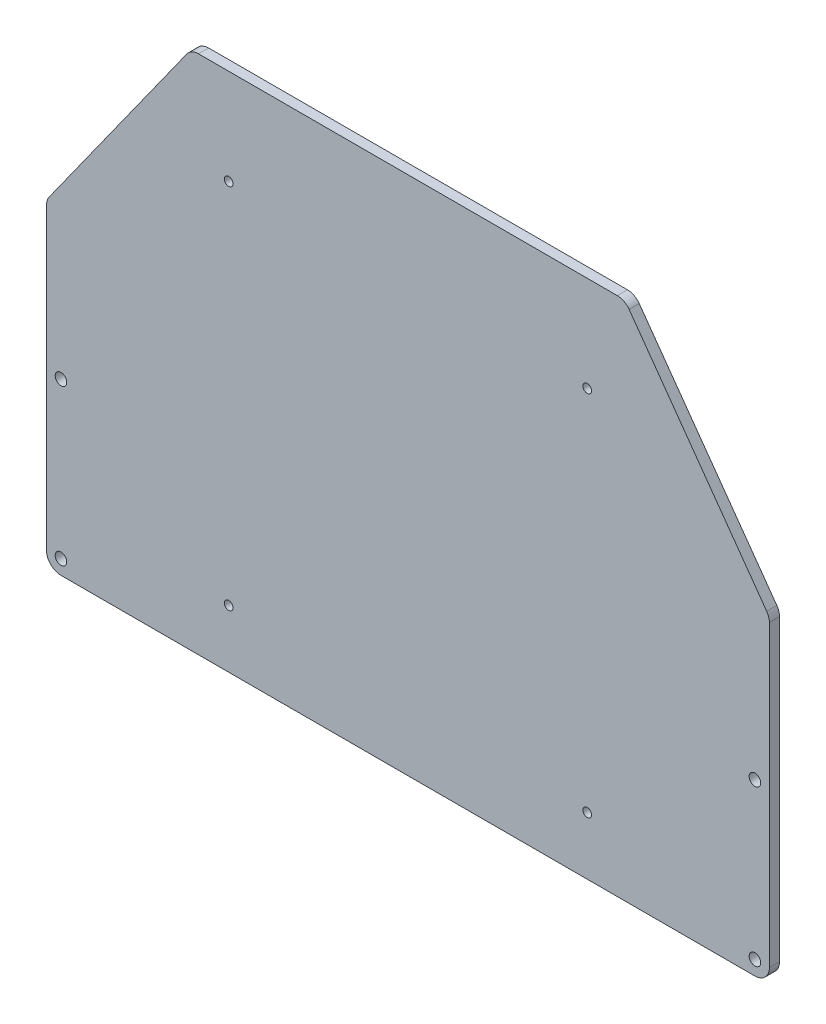
SolidWorks part; units mm, degrees
ref_plane "Plan de face" through (0, 0, 0) normal (0, 0, 1) x (1, 0, 0)
ref_plane "Plan de dessus" through (0, 0, 0) normal (0, 1, 0) x (1, 0, 0)
ref_plane "Plan de droite" through (0, 0, 0) normal (1, 0, 0) x (0, 0, -1)
sketch "Esquisse1" plane through (0, 0, 0) normal (0, 0, 1) x (1, 0, 0)
  line L1 (5, 0) -> (245, 0)
  line L2 (0, 5) -> (0, 305)
  line L3 (0, 305) -> (250, 305)
  line L4 (250, 5) -> (250, 305)
  arc A0 (250, 5) -> (245, 0) centre (245, 5) cw
  arc A1 (5, 0) -> (0, 5) centre (5, 5) cw
  point P7 (250, 0)
  point P10 (0, 0)
  dimension "D2" = 5
  dimension "D3" = 5
  dimension "D1" = 250
  dimension "D4" = 300
extrude "Boss.-Extru.1" add sketch "Esquisse1" along normal blind 3.5
sketch "Esquisse2" plane through (0, 0, 3.5) normal (0, 0, 1) x (1, 0, 0)
  line L0 (-19.0099, 5) -> (402.2953, 5) construction
  line L1 (5, 0) -> (245, 0) construction
  line L2 (5, -25.1291) -> (5, 139.966) construction
  line L3 (0, 305) -> (0, 5) construction
  line L4 (245, -22.1166) -> (245, 94.5536) construction
  line L5 (250, 5) -> (250, 305) construction
  line L6 (-9.3926, 58.8) -> (267.0784, 58.8) construction
  circle A0 centre (5, 5) radius 2
  circle A1 centre (245, 5) radius 2
  circle A2 centre (5, 58.8) radius 2
  circle A3 centre (245, 58.8) radius 2
  dimension "D1" = 4
  dimension "D2" = 4
  dimension "D7" = 4
  dimension "D8" = 4
  dimension "D3" = 5
  dimension "D4" = 5
  dimension "D5" = 5
  dimension "D6" = 53.8
extrude "Enlèv. mat.-Extru.1" cut sketch "Esquisse2" against normal through all
sketch "Esquisse3" plane through (0, 0, 3.5) normal (0, 0, 1) x (1, 0, 0)
  line L0 (0, 110) -> (50, 180)
  line L1 (50, 180) -> (200, 180)
  line L2 (200, 180) -> (250, 110)
  line L3 (125, 632.4465) -> (125, -22.4465) construction
  line L4 (250, 305) -> (0, 305) construction
  line L5 (0, 305) -> (0, 5) construction
  line L6 (250, 5) -> (250, 305) construction
  line L7 (5, 0) -> (245, 0) construction
  point P8 (125, 305)
  point P9 (125, 180)
  dimension "D1" = 110
  dimension "D2" = 110
  dimension "D3" = 150
  dimension "D4" = 180
  dimension "D5" = 180
extrude "Enlèv. mat.-Extru.2" cut sketch "Esquisse3" against normal through all and the other way through all
fillet "Congé1" radius 5 4 edges at (250, 110, 1.75) (200, 180, 1.75) (50, 180, 1.75) (0, 110, 1.75)
sketch "Esquisse4" plane through (0, 0, 0) normal (0, 0, -1) x (-1, 0, 0)
  line L0 (-125, 189.0138) -> (-125, -13.9215) construction
  line L3 (-52.5731, 180) -> (-197.4269, 180) construction
  line L4 (-5, 0) -> (-245, 0) construction
  circle A0 centre (-187, 20) radius 1.5
  circle A1 centre (-187, 147) radius 1.5
  circle A2 centre (-63, 147) radius 1.5
  circle A3 centre (-63, 20) radius 1.5
  point P8 (-125, 180)
  dimension "D3" = 3
  dimension "D4" = 3
  dimension "D5" = 3
  dimension "D6" = 3
  dimension "D1" = 124
  dimension "D2" = 124
  dimension "D7" = 127
  dimension "D8" = 127
  dimension "D9" = 20
  dimension "D10" = 62
  dimension "D11" = 20
extrude "Enlèv. mat.-Extru.3" cut sketch "Esquisse4" against normal through all
